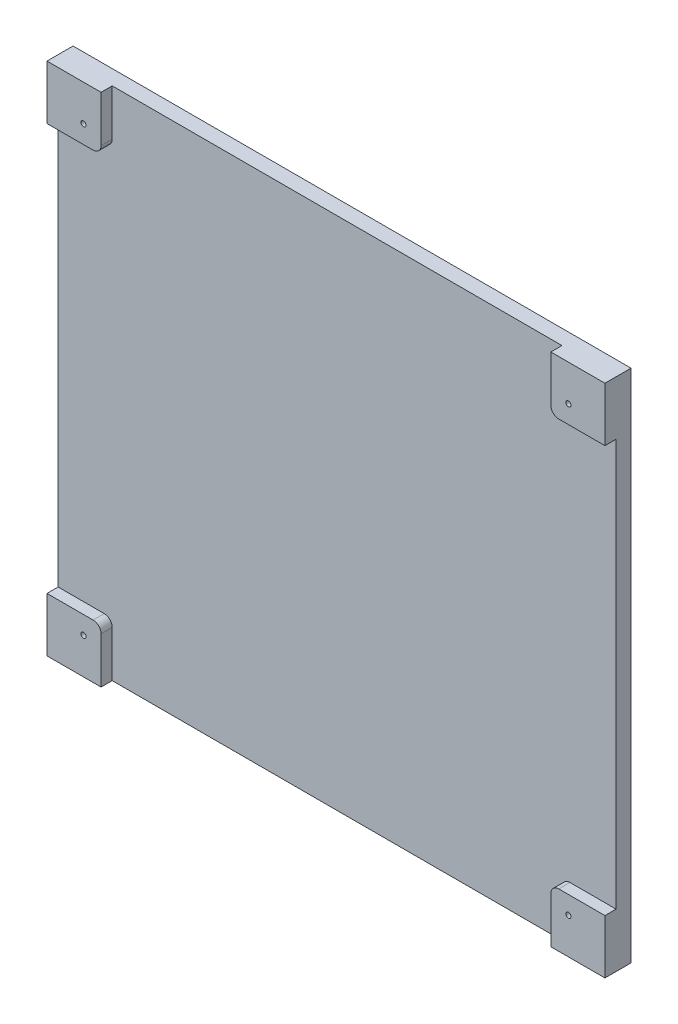
SolidWorks part; units mm, degrees
ref_plane "Front Plane" through (0, 0, 0) normal (1, 0, 0) x (0, 1, 0)
ref_plane "Top Plane" through (0, 0, 0) normal (0, 0, 1) x (0, 1, 0)
ref_plane "Right Plane" through (0, 0, 0) normal (0, 1, 0) x (-1, 0, 0)
sketch "Sketch1" plane through (0, 0, 0) normal (0, 0, 1) x (0, 1, 0)
  line L0 (-75.946, 82.677) -> (-80.946, 82.677) construction
  line L1 (-75.946, 82.677) -> (75.946, 82.677) construction
  line L2 (-75.946, 82.677) -> (-75.946, -82.677) construction
  line L3 (-75.946, -82.677) -> (75.946, -82.677) construction
  line L4 (75.946, 82.677) -> (75.946, -82.677) construction
  line L5 (-75.946, 82.677) -> (75.946, -82.677) construction
  line L6 (-75.946, -82.677) -> (75.946, 82.677) construction
  line L7 (-80.946, 87.677) -> (80.946, 87.677)
  line L8 (-80.946, 87.677) -> (-80.946, -87.677)
  line L9 (-80.946, -87.677) -> (80.946, -87.677)
  line L10 (80.946, 87.677) -> (80.946, -87.677)
  line L11 (-80.946, 87.677) -> (80.946, -87.677) construction
  line L12 (-80.946, -87.677) -> (80.946, 87.677) construction
  line L13 (-75.946, 82.677) -> (-75.946, 87.677) construction
  point P0 (0, 0)
  point P6 (0, 0)
  dimension "D1" = 151.892
  dimension "D2" = 165.354
  dimension "D3" = 5
extrude "Boss-Extrude1" add sketch "Sketch1" along normal blind 5
sketch "Sketch2" plane through (0, 0, 5) normal (0, 0, 1) x (1, 0, 0)
  line L1 (87.677, 80.946) -> (70.677, 80.946)
  line L2 (87.677, 80.946) -> (87.677, 63.946)
  line L3 (87.677, 63.946) -> (70.677, 63.946)
  line L4 (70.677, 80.946) -> (70.677, 63.946)
  line L5 (87.677, -80.946) -> (70.677, -80.946)
  line L6 (87.677, -80.946) -> (87.677, -63.946)
  line L7 (87.677, -63.946) -> (70.677, -63.946)
  line L8 (70.677, -80.946) -> (70.677, -63.946)
  line L9 (-87.677, -80.946) -> (-70.677, -80.946)
  line L10 (-87.677, -80.946) -> (-87.677, -63.946)
  line L11 (-87.677, -63.946) -> (-70.677, -63.946)
  line L12 (-70.677, -80.946) -> (-70.677, -63.946)
  line L13 (-87.677, 80.946) -> (-70.677, 80.946)
  line L14 (-87.677, 80.946) -> (-87.677, 63.946)
  line L15 (-87.677, 63.946) -> (-70.677, 63.946)
  line L16 (-70.677, 80.946) -> (-70.677, 63.946)
  line M3 (87.677, 80.946) -> (-87.677, 80.946)
  line M4 (-87.677, 80.946) -> (-87.677, -80.946)
  line M5 (-87.677, -80.946) -> (87.677, -80.946)
  line M6 (87.677, -80.946) -> (87.677, 80.946)
  dimension "D1" = 17
extrude "Boss-Extrude2" add sketch "Sketch2" along normal blind 3.5 contours L12 L11 M5 M4 | L8 L7 M5 M6 | L4 L3 M3 M6 | L16 L15 M3 M4
sketch "Sketch3" plane through (0, 0, 8.5) normal (0, 0, 1) x (1, 0, 0)
  line L2 (0, 0) -> (0, -50000) construction
  line L3 (0, 0) -> (50000, 0) construction
  circle A0 centre (-76.2, 69.596) radius 0.8
  circle A1 centre (-76.2, -69.596) radius 0.8
  circle A2 centre (76.2, -69.596) radius 0.8
  circle A3 centre (76.2, 69.596) radius 0.8
  dimension "D3" = 1.6
  dimension "D1" = 152.4
  dimension "D2" = 139.192
extrude "Cut-Extrude1" cut sketch "Sketch3" against normal through all contours A0 | A3 | A2 | A1
fillet "Fillet1" radius 2.5 4 edges at (-70.677, -63.946, 6.75) (70.677, -63.946, 6.75) (70.677, 63.946, 6.75) (-70.677, 63.946, 6.75)
chamfer "Chamfer1" distance 0.3 angle 45 8 edges at (-75.4, -69.596, 0) (77, 69.596, 0) (-87.677, 0, 0) (0, -80.946, 0) (87.677, 0, 0) (0, 80.946, 0) (-75.4, 69.596, 0) (77, -69.596, 0)
